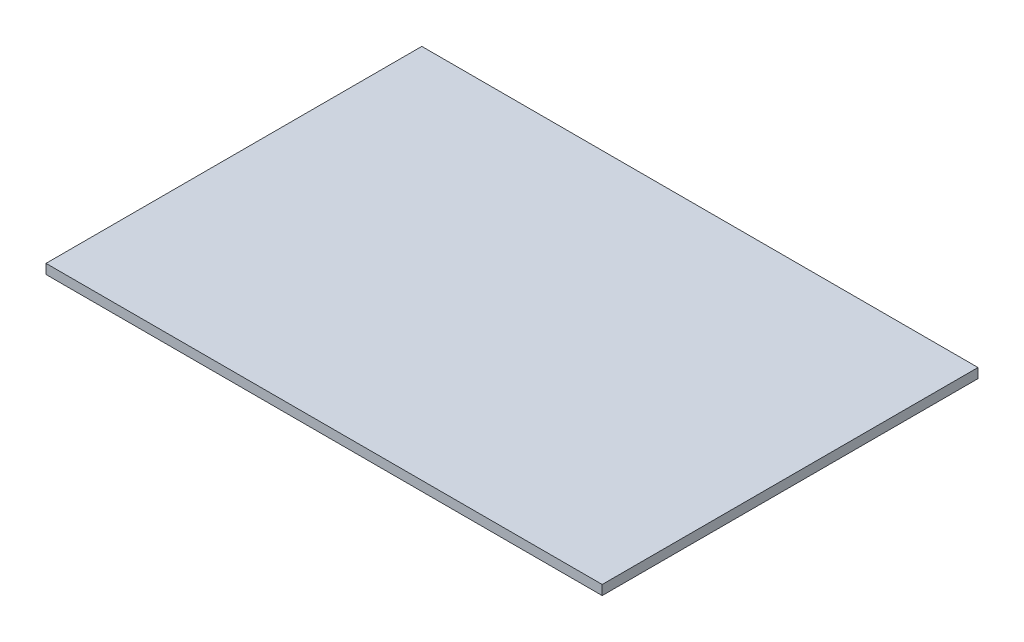
SolidWorks part; units mm, degrees
ref_plane "Front Plane" through (0, 0, 0) normal (0, 0, 1) x (1, 0, 0)
ref_plane "Top Plane" through (0, 0, 0) normal (0, 1, 0) x (1, 0, 0)
ref_plane "Right Plane" through (0, 0, 0) normal (1, 0, 0) x (0, 0, -1)
sketch "Esquisse1" plane through (0, 0, 0) normal (0, 1, 0) x (1, 0, 0)
  line L1 (-518, 350) -> (518, 350)
  line L2 (-518, 350) -> (-518, -350)
  line L3 (-518, -350) -> (518, -350)
  line L4 (518, 350) -> (518, -350)
  line L5 (-518, 350) -> (518, -350) construction
  line L6 (-518, -350) -> (518, 350) construction
  point P0 (0, 0)
extrude "Boss.-Extru.1" add sketch "Esquisse1" along normal blind 18
